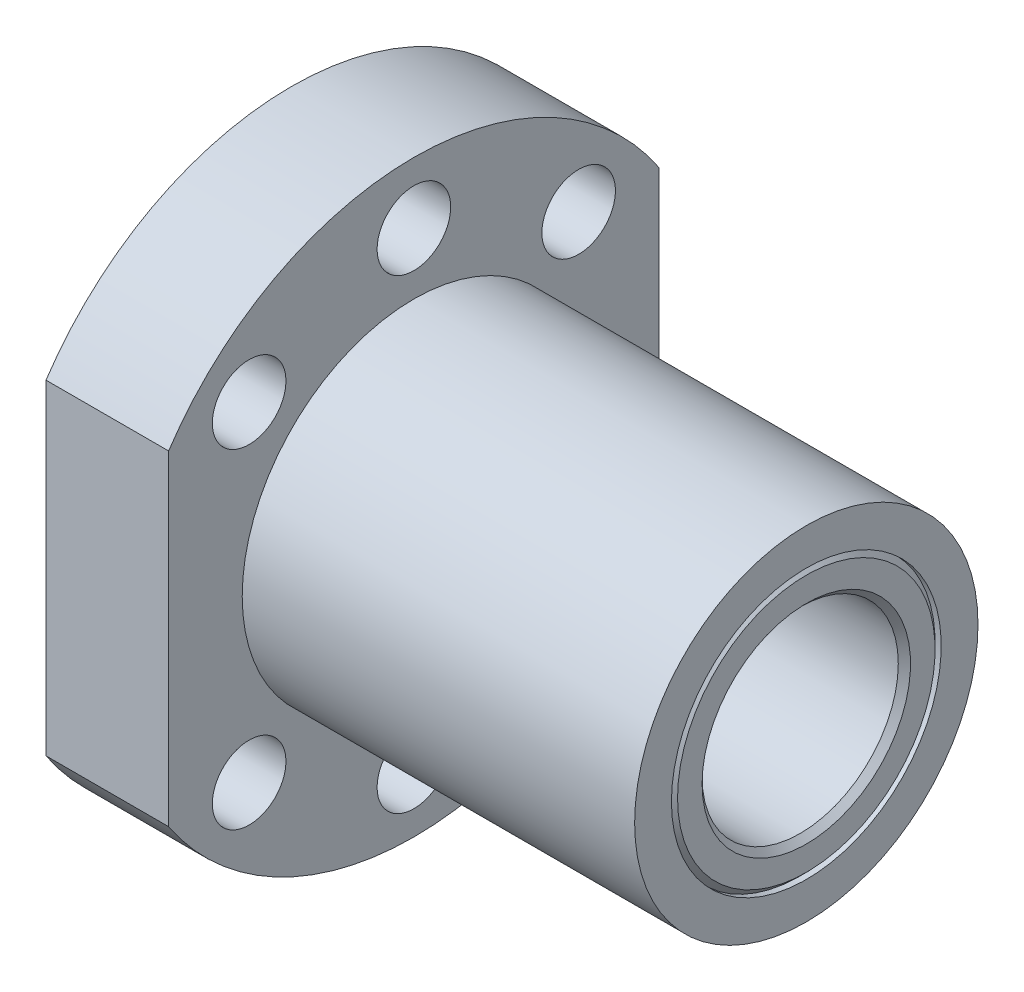
SolidWorks part; units mm, degrees
material "Литая легированная сталь"
ref_plane "Спереди" through (0, 0, 0) normal (0, 0, 1) x (1, 0, 0)
ref_plane "Сверху" through (0, 0, 0) normal (0, 1, 0) x (1, 0, 0)
ref_plane "Справа" through (0, 0, 0) normal (1, 0, 0) x (0, 0, -1)
sketch "Эскиз1" plane through (0, 0, 0) normal (0, 0, 1) x (1, 0, 0)
  line L0 (0, 11) -> (0, 24)
  line L1 (0, 24) -> (10, 24)
  line L2 (10, 24) -> (10, 14)
  line L3 (10, 14) -> (42, 14)
  line L4 (42, 14) -> (42, 11)
  line L5 (42, 11) -> (0, 11)
  line L6 (0, 0) -> (42, 0) construction
  line L7 (42, 0) -> (42, 11) construction
  dimension "D1" = 11
  dimension "D2" = 24
  dimension "D3" = 14
  dimension "D4" = 10
  dimension "D5" = 42
revolve "Повернуть1" add sketch "Эскиз1" angle 360 about L6
sketch "Эскиз2" plane through (0, 0, 0) normal (-1, 0, 0) x (0, 0, 1)
  line L0 (-30, -34) -> (-30, 34)
  line L1 (-20, -24) -> (20, -24)
  line L2 (-20, -24) -> (-20, 24)
  line L3 (-20, 24) -> (20, 24)
  line L4 (20, -24) -> (20, 24)
  line L5 (-20, -24) -> (20, 24) construction
  line L6 (-20, 24) -> (20, -24) construction
  line L7 (-30, 34) -> (30, 34)
  line L8 (30, -34) -> (30, 34)
  line L9 (-30, -34) -> (30, -34)
  circle A0 centre (0, 0) radius 24 construction
  point P0 (0, 0)
  dimension "D1" = 40
  dimension "D2" = 10
extrude "Вырез-Вытянуть1" cut sketch "Эскиз2" against normal through all
sketch "Эскиз3" plane through (0, 0, 0) normal (-1, 0, 0) x (0, 0, 1)
  line L1 (0, 19) -> (-13.435, 13.435) construction
  line L2 (-13.435, 13.435) -> (-19, 0) construction
  line L3 (-19, 0) -> (-13.435, -13.435) construction
  line L4 (-13.435, -13.435) -> (0, -19) construction
  line L5 (0, -19) -> (13.435, -13.435) construction
  line L6 (13.435, -13.435) -> (19, 0) construction
  line L7 (19, 0) -> (13.435, 13.435) construction
  line L8 (13.435, 13.435) -> (0, 19) construction
  circle A0 centre (0, 0) radius 19 construction
  circle A1 centre (0, 0) radius 17.5537 construction
  circle A2 centre (0, 19) radius 3
  circle A3 centre (13.435, 13.435) radius 3
  circle A4 centre (-13.435, 13.435) radius 3
  circle A5 centre (-13.435, -13.435) radius 3
  circle A6 centre (0, -19) radius 3
  circle A7 centre (13.435, -13.435) radius 3
  dimension "D1" = 38
  dimension "D2" = 6
  dimension "D3" = 20.8701
extrude "Вырез-Вытянуть2" cut sketch "Эскиз3" against normal through all
sketch "Эскиз4" plane through (0, 0, 0) normal (1, 0, 0) x (0, 0, -1)
  circle A0 centre (0, 0) radius 11
  circle A1 centre (0, 0) radius 8
  dimension "D1" = 16
  dimension "D2" = 22
extrude "Бобышка-Вытянуть1" add sketch "Эскиз4" along normal up to surface (42 mm away) separate body up to face at (42, 0, 14)
chamfer "Фаска1" distance 0.5 angle 45 4 edges at (0, 0, -8) (0, 0, -11) (42, 0, 11) (42, 0, 8)
